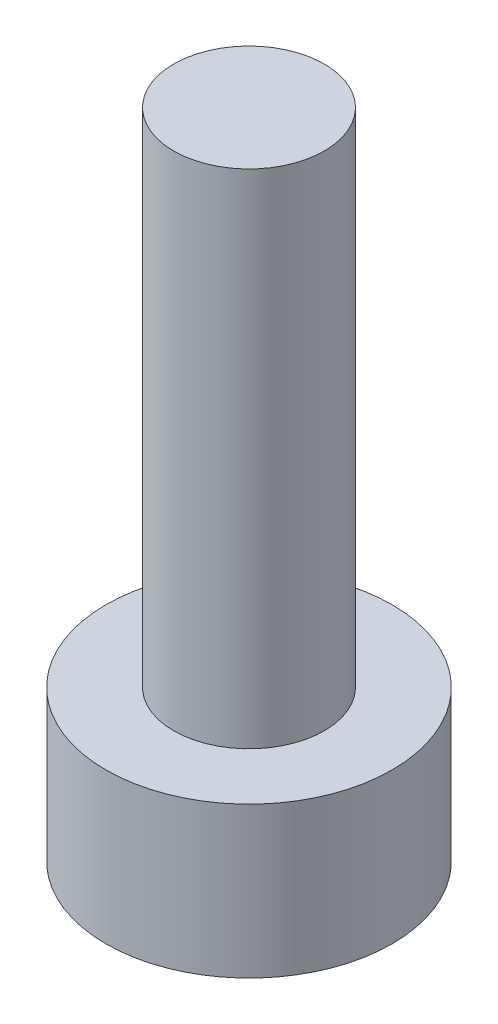
SolidWorks part; units mm, degrees
material "AISI 304"
ref_plane "前视基准面" through (0, 0, 0) normal (0, 0, 1) x (1, 0, 0)
ref_plane "上视基准面" through (0, 0, 0) normal (0, 1, 0) x (1, 0, 0)
ref_plane "右视基准面" through (0, 0, 0) normal (1, 0, 0) x (0, 0, -1)
sketch "草图1" plane through (0, 0, 0) normal (0, 0, 1) x (1, 0, 0)
  line L0 (0, 5.0793) -> (0, -4.5921) construction
  line L1 (-4.7636, 0) -> (5.5214, 0) construction
  line L2 (0, 0) -> (2.85, 0)
  line L3 (2.85, 0) -> (2.85, 3)
  line L4 (2.85, 3) -> (1.5, 3)
  line L5 (1.5, 3) -> (1.5, 13)
  line L6 (1.5, 13) -> (0, 13)
  line L7 (0, 13) -> (0, 0)
  dimension "D1" = 3
  dimension "D2" = 5.7
  dimension "D3" = 3
  dimension "D4" = 10
revolve "旋转1" add sketch "草图1" angle 360 about L0
sketch "草图2" plane through (0, 0, 0) normal (0, -1, 0) x (1, 0, 0)
  line L1 (0, -1.425) -> (1.2341, -0.7125)
  line L2 (1.2341, -0.7125) -> (1.2341, 0.7125)
  line L3 (1.2341, 0.7125) -> (0, 1.425)
  line L4 (0, 1.425) -> (-1.2341, 0.7125)
  line L5 (-1.2341, 0.7125) -> (-1.2341, -0.7125)
  line L6 (-1.2341, -0.7125) -> (0, -1.425)
  circle A0 centre (0, 0) radius 1.425 construction
  dimension "D1" = 2.85
extrude "切除-拉伸1" cut sketch "草图2" against normal blind 1.5
equation "\"长度\"= 10"
equation "\"螺钉头直径\"= 5.7"
equation "\"螺钉直径\"= 3"
equation "\"螺钉头厚度\"= 3"
equation "\"D1@草图1\"= \"螺钉直径\""
equation "\"D2@草图1\"= \"螺钉头直径\""
equation "\"D3@草图1\"= \"螺钉头厚度\""
equation "\"D4@草图1\"= \"长度\""
equation "\"D1@草图2\"= \"螺钉头直径\" * 0.5"
